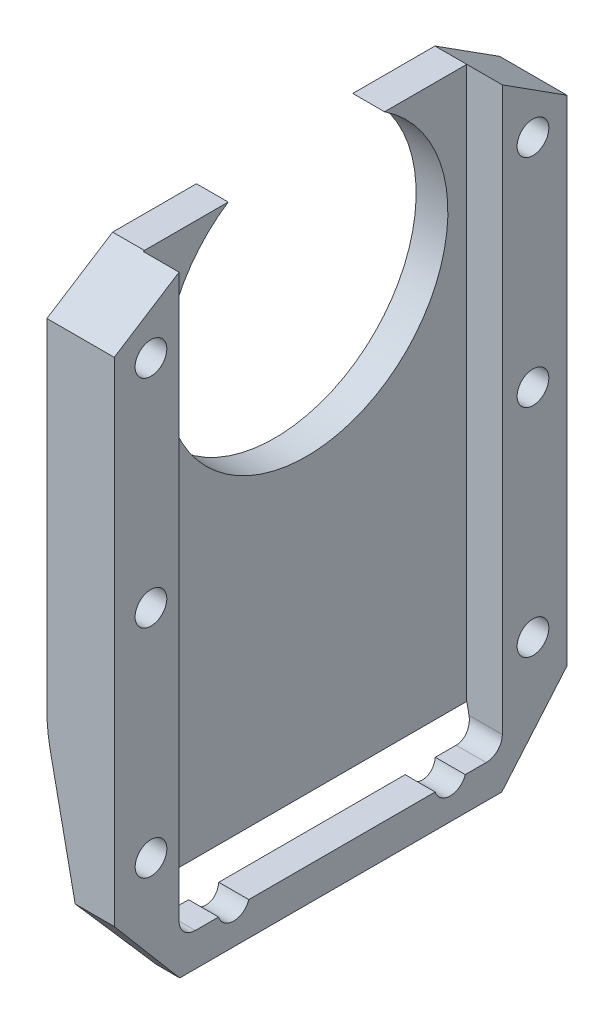
SolidWorks part; units mm, degrees
material "PLA"
ref_plane "Front Plane" through (0, 0, 0) normal (0, 0, 1) x (1, 0, 0)
ref_plane "Top Plane" through (0, 0, 0) normal (0, 1, 0) x (1, 0, 0)
ref_plane "Right Plane" through (0, 0, 0) normal (1, 0, 0) x (0, 0, -1)
sketch "Sketch1" plane through (0, 0, 0) normal (0, 0, 1) x (1, 0, 0)
  line L0 (0, 0) -> (0, 48.0727)
  line L1 (0, 48.0727) -> (-5.288, 48.0727)
  line L2 (-5.288, 48.0727) -> (-5.288, 16.8255)
  line L3 (-5.288, 16.8255) -> (-1.8137, 0)
  line L4 (-1.8137, 0) -> (0, 0)
  dimension "D1" = 5.288
  dimension "D2" = 101.667
extrude "Boss-Extrude1" add sketch "Sketch1" along normal blind 35.56
fillet "Fillet1" radius 12.7 1 edges at (-5.288, 16.8255, 17.78)
sketch "Sketch6" plane through (0, 0, 0) normal (1, 0, 0) x (0, 0, -1)
  line L0 (-17.78, 48.0727) -> (-17.78, 0) construction
  line L1 (-35.56, 48.0727) -> (0, 48.0727) construction
  line L2 (-35.56, 0) -> (0, 0) construction
  line L3 (-17.78, -971.6385) -> (-17.78, 49028.3615) construction
  line L4 (-30.47, 48.0727) -> (-5.086, 48.0727)
  line L5 (-30.47, 48.0727) -> (-30.47, 2.6227)
  line L6 (-30.47, 2.6227) -> (-5.086, 2.6227)
  line L7 (-5.086, 48.0727) -> (-5.086, 2.6227)
  dimension "D1" = 45.45
  dimension "D2" = 25.384
  dimension "D3" = 12.69
  dimension "0" = 0
extrude "Cut-Extrude1" cut sketch "Sketch6" against normal blind 2.794
fillet "Fillet2" radius 1.27 2 edges at (-1.1777, 2.6227, 30.47) (-1.1777, 2.6227, 5.086)
sketch "Sketch10" plane through (0, 0, 0) normal (1, 0, 0) x (0, 0, -1)
  line L0 (-35.56, 44.7804) -> (-30.3976, 48.0727)
  line L1 (-35.56, 0) -> (-35.56, 48.0727) construction
  line L2 (-35.56, 48.0727) -> (-30.47, 48.0727) construction
  line L3 (-30.3976, 48.0727) -> (-35.56, 48.0727)
  line L4 (-35.56, 48.0727) -> (-35.56, 44.7804)
extrude "Cut-Extrude3" cut sketch "Sketch10" against normal through all
sketch "Sketch11" plane through (0, 0, 0) normal (1, 0, 0) x (0, 0, -1)
  line L0 (-5.0855, 48.0727) -> (0, 48.0727)
  line L1 (-5.086, 48.0727) -> (0, 48.0727) construction
  line L2 (0, 48.0727) -> (0, 44.8249)
  line L3 (0, 0) -> (0, 48.0727) construction
  line L4 (0, 44.8249) -> (-5.0855, 48.0727)
  line L5 (0, 6.0295) -> (-5.1287, 0)
  line L6 (-35.56, 0) -> (0, 0) construction
  line L7 (-5.1287, 0) -> (0, 0)
  line L8 (0, 0) -> (0, 6.0295)
  line L9 (-35.56, 6.0712) -> (-35.56, 0)
  line L10 (-35.56, 0) -> (-35.56, 44.7804) construction
  line L11 (-35.56, 0) -> (-30.4171, 0)
  line L12 (-30.4171, 0) -> (-35.56, 6.0712)
extrude "Cut-Extrude4" cut sketch "Sketch11" against normal through all
hole_wizard "7/8 (0.875) Diameter Hole1" positions "Sketch12" profile "Sketch13" hole size "7/8" standard "ANSI Inch" end condition through all
sketch "Sketch12" plane through (-5.288, 0, 0) normal (-1, 0, 0) x (0, 0, 1)
  point P0 (17.6785, 38.8095)
sketch "Sketch13" plane through (-5.288, 38.8095, 17.6785) normal (0, 1, 0) x (0, 0, 1)
  line L0 (0, 0) -> (0, 5.288)
  line L1 (0, 5.288) -> (11.1125, 5.288)
  line L2 (11.1125, 5.288) -> (11.1125, 0)
  line L5 (11.1125, 0) -> (0, 0)
  line L11 (0, -6.35) -> (0, 107.95) construction
  dimension "Thru Hole Dia." = 22.225
  dimension "Thru Hole Depth" = 5.288
hole_wizard "#40 (0.098) Diameter Hole1" positions "Sketch14" profile "Sketch15" hole size "#40" standard "ANSI Inch" end condition through all
sketch "Sketch14" plane through (-5.288, 0, 0) normal (-1, 0, 0) x (0, 0, 1)
  point P0 (2.6785, 43.3095)
  point P3 (2.6785, 26.3095)
  point P6 (2.6785, 9.3095)
  point P9 (9.1785, 3.0095)
  point P12 (26.1819, 2.9992)
  point P14 (32.6729, 9.2992)
  point P16 (32.6785, 26.3095)
  point P19 (32.6785, 43.2992)
sketch "Sketch15" plane through (-5.288, 43.3095, 2.6785) normal (0, 1, 0) x (0, 0, 1)
  line L0 (0, 0) -> (0, 5.288)
  line L1 (0, 5.288) -> (1.2446, 5.288)
  line L2 (1.2446, 5.288) -> (1.2446, 0.635)
  line L3 (1.2446, 0.635) -> (1.8796, 0)
  line L5 (1.8796, 0) -> (0, 0)
  line L6 (-1.2446, 0.635) -> (-1.8796, 0) construction
  line L11 (0, -6.35) -> (0, 107.95) construction
  dimension "Thru Hole Dia." = 2.4892
  dimension "Thru Hole Depth" = 5.288
  dimension "Near C'Sink Dia." = 3.7592
  dimension "Near C'Sink Angle" = 90
sketch "Sketch17" plane through (-5.288, 0, 0) normal (-1, 0, 0) x (0, 0, 1)
  line L0 (6.566, 38.8095) -> (28.791, 38.8095) construction
  circle A0 centre (17.6785, 38.8095) radius 11.1125 construction
  circle A1 centre (17.6785, 38.8095) radius 11.1125
  point P7 (17.6785, 38.8095)
